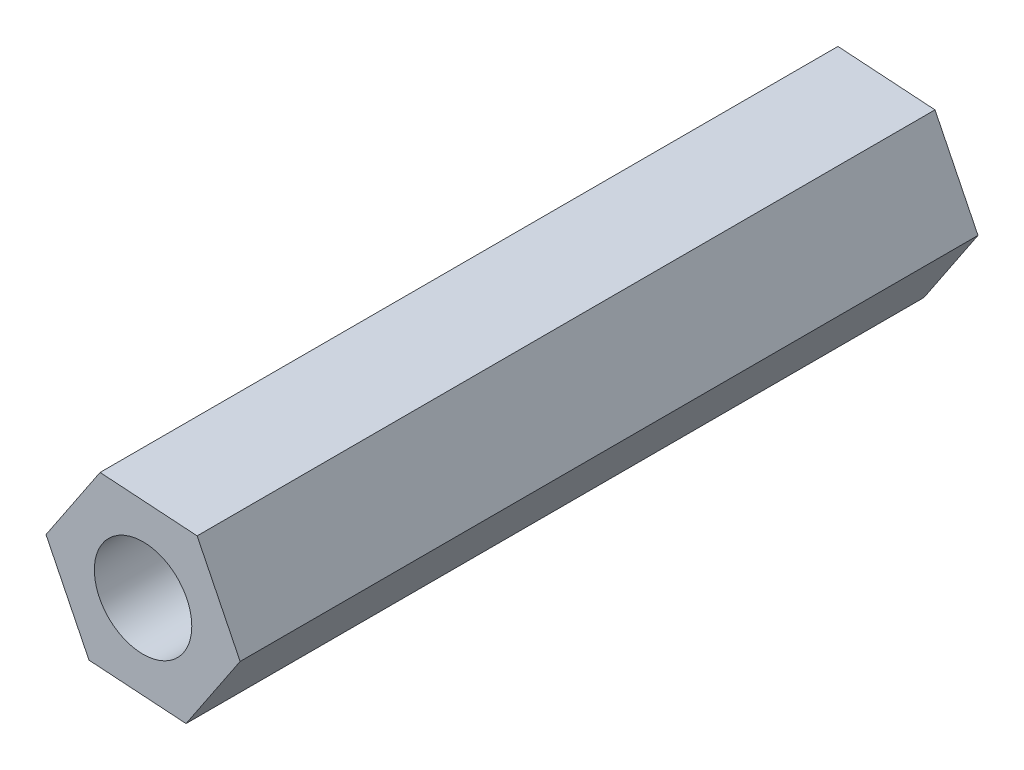
SolidWorks part; units mm, degrees
ref_plane "Front Plane" through (0, 0, 0) normal (0, 0, 1) x (1, 0, 0)
ref_plane "Top Plane" through (0, 0, 0) normal (0, 1, 0) x (1, 0, 0)
ref_plane "Right Plane" through (0, 0, 0) normal (1, 0, 0) x (0, 0, -1)
sketch "Sketch1" plane through (0, 0, 0) normal (0, 0, 1) x (1, 0, 0)
  line L1 (631.9836, -1285.3343) -> (630.1516, -1288.0739)
  line L2 (630.1516, -1288.0739) -> (631.6081, -1291.0303)
  line L3 (631.6081, -1291.0303) -> (634.8966, -1291.2471)
  line L4 (634.8966, -1291.2471) -> (636.7287, -1288.5075)
  line L5 (636.7287, -1288.5075) -> (635.2722, -1285.5511)
  line L6 (635.2722, -1285.5511) -> (631.9836, -1285.3343)
  circle A0 centre (633.4401, -1288.2907) radius 2.8542 construction
  circle A2 centre (633.4401, -1288.2907) radius 1.651
extrude "Boss-Extrude1" add sketch "Sketch1" along normal blind 25
